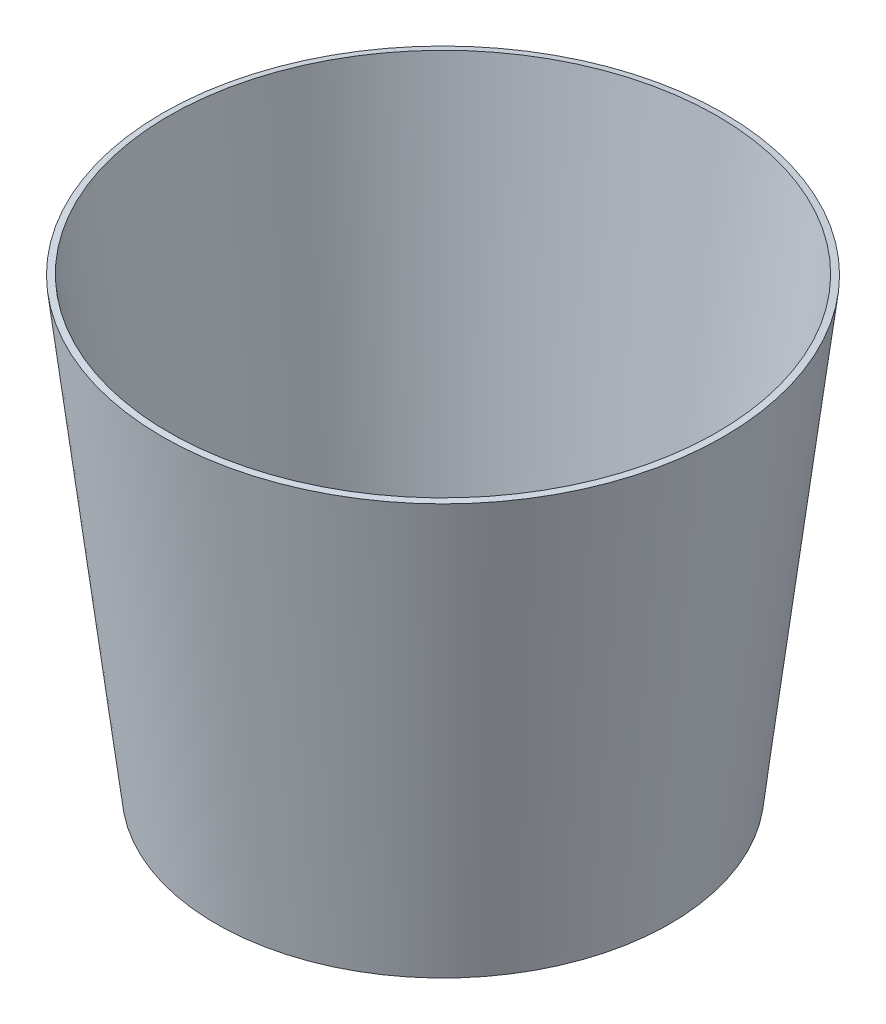
SolidWorks part; units mm, degrees
ref_plane "前基準面" through (0, 0, 0) normal (0, 0, 1) x (1, 0, 0)
ref_plane "上基準面" through (0, 0, 0) normal (0, 1, 0) x (1, 0, 0)
ref_plane "右基準面" through (0, 0, 0) normal (1, 0, 0) x (0, 0, -1)
sketch "草圖1" plane through (0, 0, 0) normal (0, 0, 1) x (1, 0, 0)
  line L1 (0, 0) -> (107.664, 0)
  line L2 (0, 0) -> (0, 3)
  line L3 (0, 3) -> (105, 3)
  line L5 (105, 3) -> (130, 213)
  line L6 (107.664, 0) -> (132.979, 212.6454)
  line L7 (130, 213) -> (132.979, 212.6454)
  dimension "D1" = 105
  dimension "D2" = 130
  dimension "D3" = 3
  dimension "D4" = 3
  dimension "D5" = 210
revolve "旋轉1" add sketch "草圖1" angle 360 about L2
